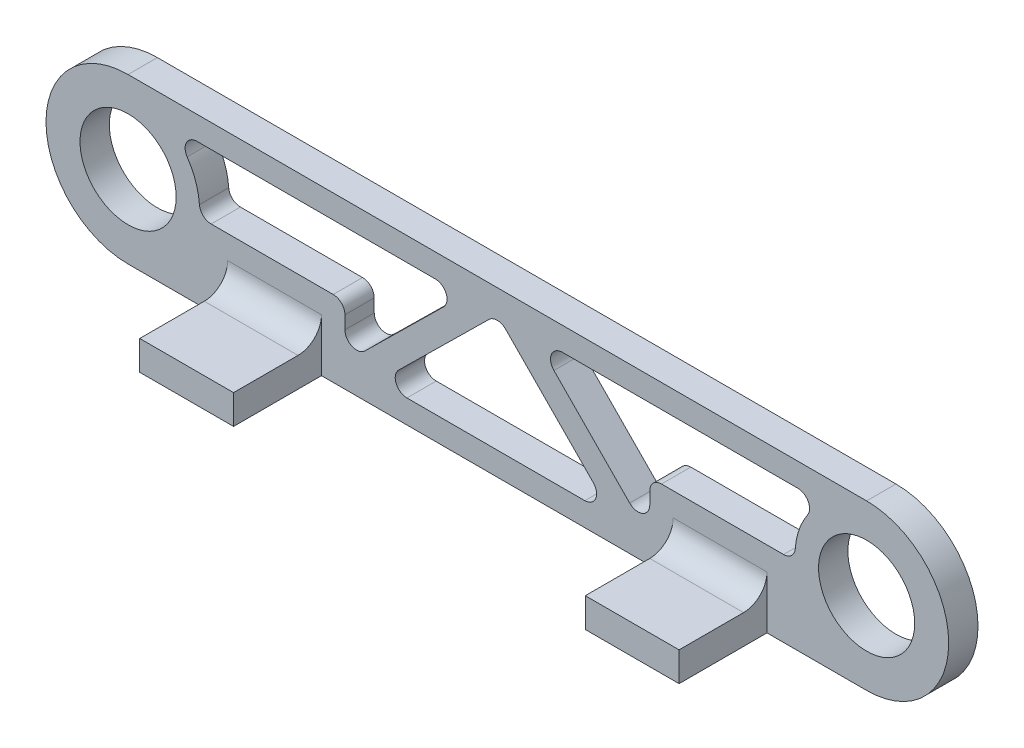
SolidWorks part; units mm, degrees
ref_plane "Front Plane" through (0, 0, 0) normal (0, 0, 1) x (1, 0, 0)
ref_plane "Top Plane" through (0, 0, 0) normal (0, 1, 0) x (1, 0, 0)
ref_plane "Right Plane" through (0, 0, 0) normal (1, 0, 0) x (0, 0, -1)
sketch "Sketch1" plane through (0, 0, 0) normal (0, 0, 1) x (1, 0, 0)
  line L0 (-40, 0) -> (40, 0) construction
  line L1 (-40, 8.89) -> (40, 8.89)
  line L2 (-40, -8.89) -> (40, -8.89)
  line L3 (-40, 0) -> (40, 0) construction
  arc A0 (-40, 8.89) -> (-40, -8.89) centre (-40, 0) ccw
  arc A1 (40, -8.89) -> (40, 8.89) centre (40, 0) ccw
  circle A2 centre (-40, 0) radius 5.207
  circle A3 centre (40, 0) radius 5.207
  point P2 (0, 0)
  point P7 (38.1, 0)
  dimension "D2" = 8.89
  dimension "D3" = 10.414
  dimension "D1" = 80
  dimension "D5" = 80
  dimension "D4" = 2
extrude "Boss-Extrude1" add sketch "Sketch1" along normal blind 3.175
sketch "Sketch2" plane through (0, 0, 0) normal (0, 0, 1) x (1, 0, 0)
  line L0 (-40, -8.89) -> (40, -8.89) construction
  line L5 (40, 0) -> (-40, 0) construction
  line L7 (0, -1.7463) -> (0, 1.7463) construction
  line L8 (19.05, -8.89) -> (29.21, -8.89)
  line L9 (29.21, -5.715) -> (29.21, -8.89)
  line L10 (19.05, -5.715) -> (29.21, -5.715)
  line L11 (19.05, -5.715) -> (19.05, -8.89)
  line L12 (-19.05, -5.715) -> (-29.21, -5.715)
  line L13 (-19.05, -5.715) -> (-19.05, -8.89)
  line L14 (-19.05, -8.89) -> (-29.21, -8.89)
  line L15 (-29.21, -5.715) -> (-29.21, -8.89)
  point P2 (-22.1074, -5.715)
  dimension "D1" = 10.16
  dimension "D2" = 3.175
  dimension "D3" = 19.05
extrude "Boss-Extrude2" add sketch "Sketch2" along normal blind 12.7
fillet "Fillet1" radius 2.54 2 edges at (-24.13, -5.715, 3.175) (24.13, -5.715, 3.175)
sketch "Sketch3" plane through (0, 0, 3.175) normal (0, 0, 1) x (1, 0, 0)
  line L4 (-31.75, -0.635) -> (-32.2791, -0.635)
  line L5 (31.75, -0.635) -> (32.2791, -0.635)
  line L6 (-16.51, -6.35) -> (-3.6192, 6.35)
  line L7 (-12.8908, -6.35) -> (0, 6.35)
  line L8 (-3.6192, 6.35) -> (-35.5623, 6.35)
  line L9 (0, 6.35) -> (12.512, -6.35)
  line L10 (16.51, -6.35) -> (3.998, 6.35)
  line L26 (-31.75, -0.635) -> (-16.51, -0.635)
  line L27 (-16.51, -0.635) -> (-16.51, -6.35)
  line L28 (-16.51, -6.35) -> (16.51, -6.35)
  line L29 (16.51, -6.35) -> (16.51, -0.635)
  line L37 (16.51, -0.635) -> (31.75, -0.635)
  line L38 (31.75, -0.635) -> (31.75, -6.35)
  line L39 (31.75, -6.35) -> (40, -6.35)
  line L40 (40, 6.35) -> (-40, 6.35)
  line L41 (-40, -6.35) -> (-31.75, -6.35)
  line L42 (-31.75, -6.35) -> (-31.75, -0.635)
  line L43 (-31.75, -0.635) -> (-16.51, -0.635)
  line L44 (-16.51, -0.635) -> (-16.51, -6.35)
  line L45 (-12.8908, -6.35) -> (12.512, -6.35)
  line L46 (16.51, -6.35) -> (16.51, -0.635)
  line L47 (16.51, -0.635) -> (31.75, -0.635)
  line L50 (35.5623, 6.35) -> (3.998, 6.35)
  circle A4 centre (40, 0) radius 7.747
  arc A5 (35.5623, 6.35) -> (32.2791, -0.635) centre (40, 0) ccw
  arc A18 (40, -6.35) -> (40, 6.35) centre (40, 0) ccw
  arc A19 (-40, 6.35) -> (-40, -6.35) centre (-40, 0) ccw
  circle A22 centre (-40, 0) radius 7.747
  arc A23 (-32.2791, -0.635) -> (-35.5623, 6.35) centre (-40, 0) ccw
  point P1 (12.512, -6.35)
  point P16 (0, 0)
  point P17 (0, 6.35)
  point P18 (0, 0)
  dimension "D2" = 2.54
  dimension "D3" = 2.54
  dimension "D4" = 2.54
  dimension "D1" = 2.54
extrude "Cut-Extrude1" cut sketch "Sketch3" against normal through all
fillet "Fillet2" radius 1.27 13 edges at (35.5623, 6.35, 1.5875) (32.2791, -0.635, 1.5875) (16.51, -0.635, 1.5875) (-16.51, -0.635, 1.5875) (-32.2791, -0.635, 1.5875) (16.51, -6.35, 1.5875) (3.998, 6.35, 1.5875) (12.512, -6.35, 1.5875) (-3.6192, 6.35, 1.5875) (0, 6.35, 1.5875) (-12.8908, -6.35, 1.5875) (-16.51, -6.35, 1.5875) (-35.5623, 6.35, 1.5875)
